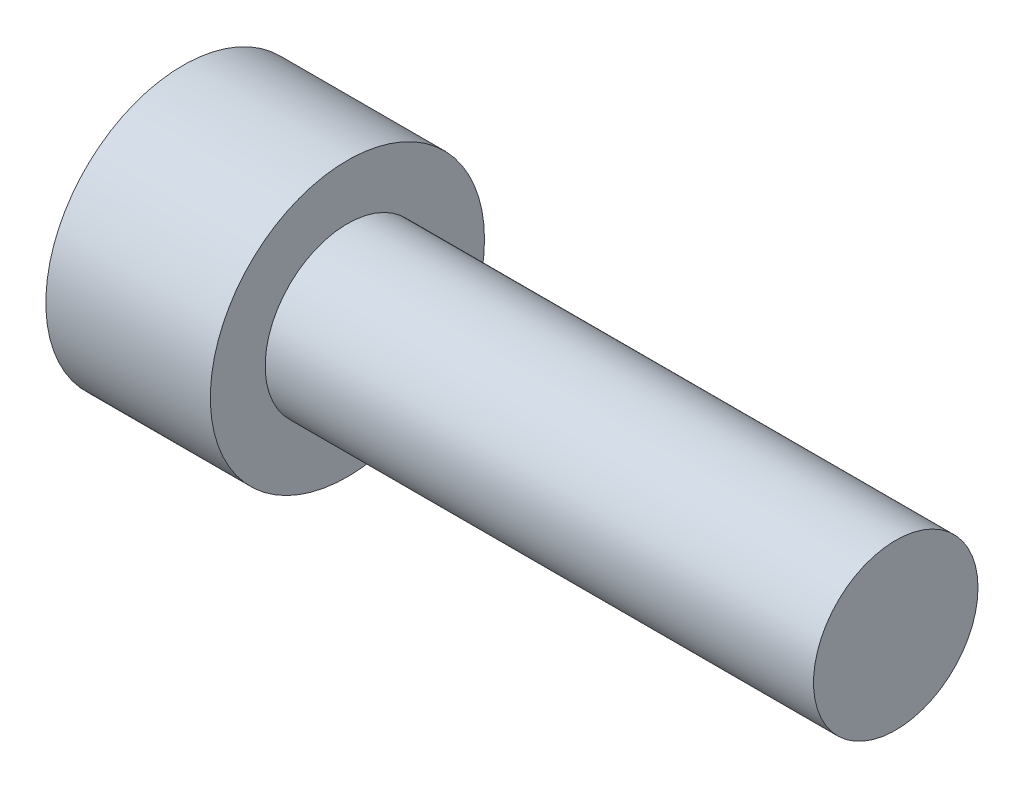
SolidWorks part; units mm, degrees
ref_plane "Front Plane" through (0, 0, 0) normal (0, 0, 1) x (1, 0, 0)
ref_plane "Top Plane" through (0, 0, 0) normal (0, 1, 0) x (1, 0, 0)
ref_plane "Right Plane" through (0, 0, 0) normal (1, 0, 0) x (0, 0, -1)
sketch "Sketch1" plane through (0, 0, 0) normal (0, 1, 0) x (1, 0, 0)
  line L0 (0, 0) -> (0, 2.5)
  line L1 (0, 2.5) -> (3, 2.5)
  line L2 (3, 2.5) -> (3, 1.5)
  line L3 (3, 1.5) -> (13, 1.5)
  line L4 (13, 1.5) -> (13, 0)
  line L5 (13, 0) -> (0, 0)
  dimension "D1" = 3
  dimension "D2" = 2.5
  dimension "D3" = 1.5
  dimension "D4" = 10
revolve "Revolve1" add sketch "Sketch1" angle 360 about L5
